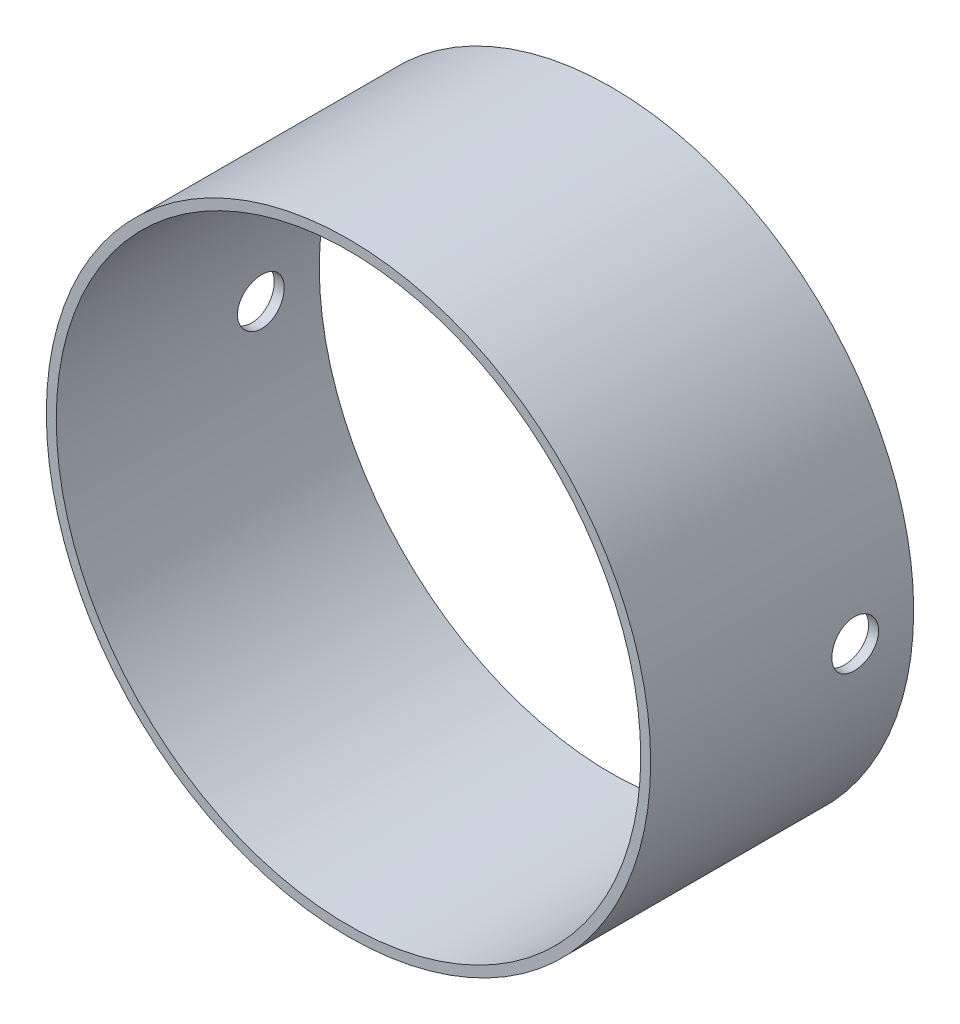
SolidWorks part; units mm, degrees
material "PVC 0.007 Plasticized"
ref_plane "Front Plane" through (0, 0, 0) normal (0, 0, 1) x (1, 0, 0)
ref_plane "Top Plane" through (0, 0, 0) normal (0, 1, 0) x (1, 0, 0)
ref_plane "Right Plane" through (0, 0, 0) normal (1, 0, 0) x (0, 0, -1)
sketch "Sketch1" plane through (0, 0, 0) normal (0, 0, 1) x (1, 0, 0)
  circle A0 centre (0, 0) radius 50
  circle A1 centre (0, 0) radius 51.7
  dimension "D1" = 100
  dimension "D2" = 103.4
  dimension "D3" = 1.7
extrude "Boss-Extrude1" add sketch "Sketch1" along normal blind 35 and the other way blind 10
sketch "Sketch2" plane through (0, 0, 0) normal (1, 0, 0) x (0, 0, -1)
  circle A0 centre (0, 0) radius 4
  dimension "D1" = 8
extrude "Cut-Extrude1" cut sketch "Sketch2" against normal up to surface and the other way up to surface up to face at (51.7, 0, -10) other way up to face at (51.7, 0, -10)
